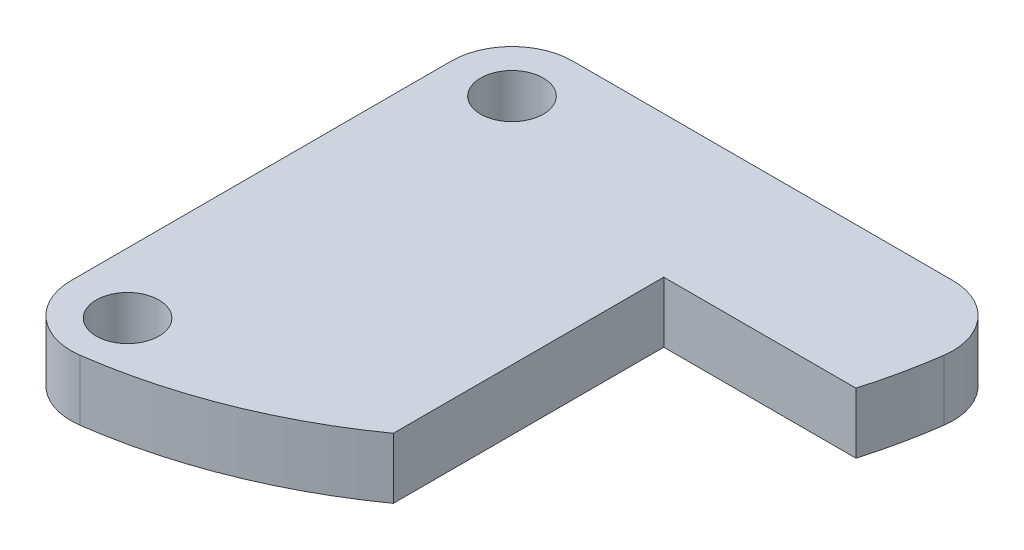
SolidWorks part; units mm, degrees
ref_plane "Front Plane" through (0, 0, 0) normal (0, 0, 1) x (1, 0, 0)
ref_plane "Top Plane" through (0, 0, 0) normal (0, 1, 0) x (1, 0, 0)
ref_plane "Right Plane" through (0, 0, 0) normal (1, 0, 0) x (0, 0, -1)
sketch "Sketch1" plane through (0, 0, 0) normal (0, 1, 0) x (1, 0, 0)
  line L1 (-12.5, -12.5) -> (12.5, -12.5)
  line L2 (-12.5, -12.5) -> (-12.5, 12.5)
  line L3 (-12.5, 12.5) -> (12.5, 12.5)
  line L4 (12.5, -12.5) -> (12.5, 12.5)
  line L5 (-12.5, -12.5) -> (12.5, 12.5) construction
  line L6 (-12.5, 12.5) -> (12.5, -12.5) construction
  circle A0 centre (-9.5, 9.5) radius 1.55
  circle A1 centre (-9.5, -9.5) radius 1.55
  point P0 (0, 0)
  dimension "D3" = 3.1
  dimension "D1" = 25
  dimension "D2" = 25
  dimension "D4" = 3
  dimension "D5" = 2
extrude "Boss-Extrude1" add sketch "Sketch1" against normal blind 3
sketch "Sketch2" plane through (0, 0, 0) normal (0, 1, 0) x (1, 0, 0)
  line L0 (12.5, 12.5) -> (-12.5, 12.5) construction
  line L1 (12.5, -12.5) -> (2, -12.5)
  line L2 (12.5, -12.5) -> (12.5, 5.5)
  line L3 (12.5, 5.5) -> (2, 5.5)
  line L4 (2, -12.5) -> (2, 5.5)
  line L5 (-12.5, 12.5) -> (-12.5, -12.5) construction
  dimension "D1" = 7
  dimension "D2" = 14.5
extrude "Cut-Extrude1" cut sketch "Sketch2" against normal through all
sketch "Sketch3" plane through (0, 0, 0) normal (0, 1, 0) x (1, 0, 0)
  line L0 (-12.5, 12.5) -> (-12.5, -12.5) construction
  line L1 (-12.5, -12.5) -> (12.5, -12.5)
  line L2 (12.5, -12.5) -> (12.5, 12.5)
  arc A0 (12.5, 12.5) -> (-12.5, -12.5) centre (-12.5, 12.5) cw
extrude "Cut-Extrude2" cut sketch "Sketch3" against normal through all
fillet "Fillet2" radius 3 3 edges at (-12.5, -1.5, -12.5) (12.5, -1.5, -12.5) (-12.5, -1.5, 12.5)
